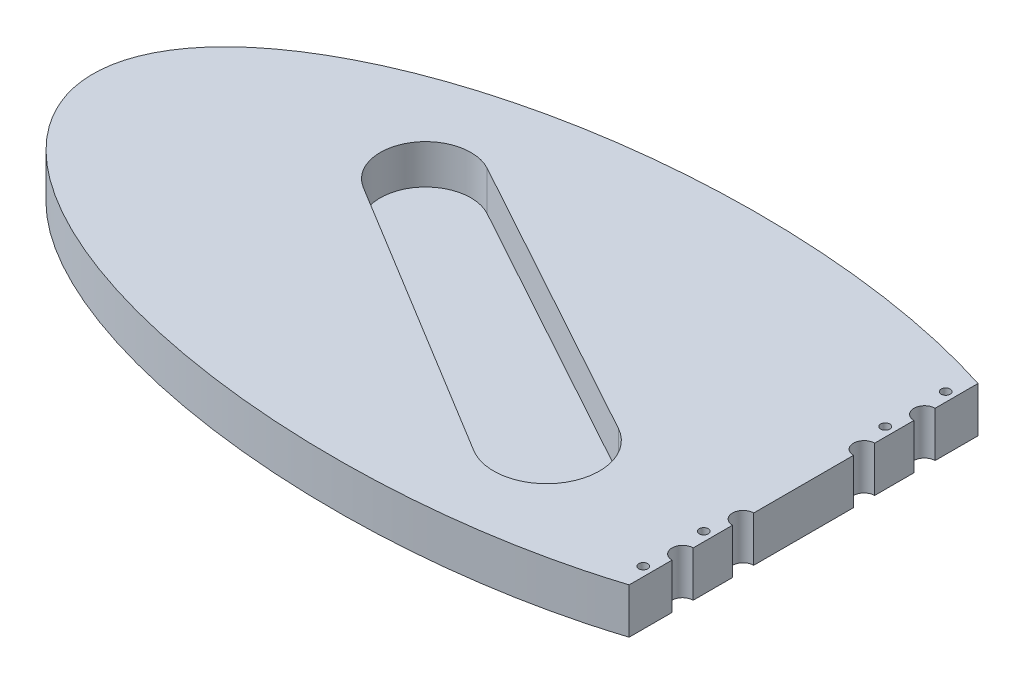
SolidWorks part; units mm, degrees
ref_plane "Front Plane" through (0, 0, 0) normal (0, 0, 1) x (1, 0, 0)
ref_plane "Top Plane" through (0, 0, 0) normal (0, 1, 0) x (1, 0, 0)
ref_plane "Right Plane" through (0, 0, 0) normal (1, 0, 0) x (0, 0, -1)
sketch "Sketch1" plane through (0, 0, 0) normal (0, 1, 0) x (1, 0, 0)
  line L0 (85, 57.6763) -> (85, -57.6763)
  ellipse E0 centre (0, 0) end of major axis (-150, 0) minor radius 70 (85, 57.6763) -> (85, -57.6763) ccw
  dimension "D1" = 150
  dimension "D2" = 70
  dimension "D3" = 85
extrude "Boss-Extrude1" add sketch "Sketch1" along normal blind 15
sketch "Sketch2" plane through (0, 15, 0) normal (0, 1, 0) x (1, 0, 0)
  line L0 (-57.782, 38.1492) -> (38.4209, -14.6593)
  line L1 (-72.8092, 12.1931) -> (20.8892, -44.9413)
  line L2 (-150, 0) -> (150, 0) construction
  line L3 (0, 70) -> (0, -70) construction
  arc A0 (-57.782, 38.1492) -> (-72.8092, 12.1931) centre (-65, 25) ccw
  arc A1 (20.8892, -44.9413) -> (38.4209, -14.6593) centre (30, -30) ccw
  ellipse E0 centre (0, 0) end of major axis (-150, 0) minor radius 70 construction
  dimension "D1" = 30
  dimension "D2" = 35
  dimension "D3" = 65
  dimension "D4" = 25
  dimension "D5" = 30
  dimension "D6" = 30
extrude "Cut-Extrude1" cut sketch "Sketch2" against normal blind 13
sketch "Sketch3" plane through (0, 15, 0) normal (0, 1, 0) x (1, 0, 0)
  line L0 (82, 58.6145) -> (82, -58.6145) construction
  line L1 (85, -57.6763) -> (85, 57.6763) construction
  line L2 (-150, 0) -> (85, 0) construction
  circle A0 centre (85, 40) radius 3.5
  circle A1 centre (85, 20) radius 3.5
  circle A2 centre (82, 30) radius 1.5
  circle A3 centre (82, 50) radius 1.5
  circle A4 centre (82, -50) radius 1.5
  circle A5 centre (85, -40) radius 3.5
  circle A6 centre (82, -30) radius 1.5
  circle A7 centre (85, -20) radius 3.5
  ellipse E0 centre (0, 0) end of major axis (-150, 0) minor radius 70 (85, 57.6763) -> (85, -57.6763) ccw construction
  dimension "D2" = 7
  dimension "D6" = 3
  dimension "D7" = 3
  dimension "D1" = 3
  dimension "D3" = 20
  dimension "D4" = 20
  dimension "D5" = 30
  dimension "D8" = 20
extrude "Cut-Extrude2" cut sketch "Sketch3" against normal through all
